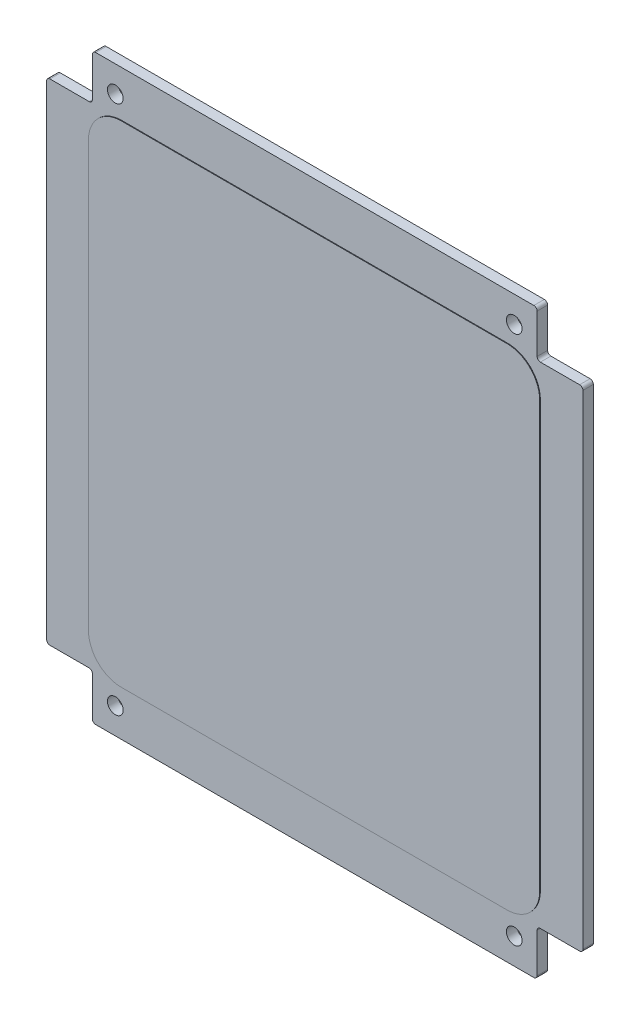
SolidWorks part; units mm, degrees
material "PET"
ref_plane "Front Plane" through (0, 0, 0) normal (0, 0, 1) x (1, 0, 0)
ref_plane "Top Plane" through (0, 0, 0) normal (0, 1, 0) x (1, 0, 0)
ref_plane "Right Plane" through (0, 0, 0) normal (1, 0, 0) x (0, 0, -1)
sketch "Sketch1" plane through (0, 0, 0) normal (0, 0, 1) x (1, 0, 0)
  line L0 (-34, 44) -> (-34, 38)
  line L1 (-33.5, -44.5) -> (33.5, -44.5)
  line L2 (-41, 37) -> (-41, -37)
  line L3 (-33.5, 44.5) -> (33.5, 44.5)
  line L4 (41, -37) -> (41, 37)
  line L5 (34, -44) -> (34, -38)
  line L6 (34.5, -37.5) -> (40.5, -37.5)
  line L7 (-34.5, 37.5) -> (-40.5, 37.5)
  line L8 (34, 44) -> (34, 38)
  line L9 (34.5, 37.5) -> (40.5, 37.5)
  line L10 (-40.5, -37.5) -> (-34.5, -37.5)
  line L11 (-34, -38) -> (-34, -44)
  line L12 (-34.5, -38) -> (34.5, 38) construction
  line L13 (34.5, -38) -> (-34.5, 38) construction
  arc A0 (-33.5, 44.5) -> (-34, 44) centre (-33.5, 44) ccw
  arc A1 (33.5, 44.5) -> (34, 44) centre (33.5, 44) cw
  arc A2 (34, 38) -> (34.5, 37.5) centre (34.5, 38) ccw
  arc A3 (40.5, 37.5) -> (41, 37) centre (40.5, 37) cw
  arc A4 (33.5, -44.5) -> (34, -44) centre (33.5, -44) ccw
  arc A5 (34.5, -37.5) -> (34, -38) centre (34.5, -38) ccw
  arc A6 (40.5, -37.5) -> (41, -37) centre (40.5, -37) ccw
  arc A7 (-34, -44) -> (-33.5, -44.5) centre (-33.5, -44) ccw
  arc A8 (-34, -38) -> (-34.5, -37.5) centre (-34.5, -38) ccw
  arc A9 (-41, -37) -> (-40.5, -37.5) centre (-40.5, -37) ccw
  arc A10 (-40.5, 37.5) -> (-41, 37) centre (-40.5, 37) ccw
  arc A11 (-34.5, 37.5) -> (-34, 38) centre (-34.5, 38) ccw
  point P0 (0, 0)
  dimension "D4" = 0.5
  dimension "D1" = 7
  dimension "D2" = 7
  dimension "D3" = 7
  dimension "D5" = 7
  dimension "D6" = 7
  dimension "D7" = 7
  dimension "D8" = 7
  dimension "D9" = 7
  dimension "D10" = 89
  dimension "D11" = 82
extrude "Boss-Extrude1" add sketch "Sketch1" along normal blind 1.6
sketch "Esboço1" plane through (0, 0, 1.6) normal (0, 0, 1) x (1, 0, 0)
  line L1 (-29.5, -37.5) -> (29.5, -37.5)
  line L2 (-34.5, -32.5) -> (-34.5, 32.5)
  line L3 (-29.5, 37.5) -> (29.5, 37.5)
  line L4 (34.5, -32.5) -> (34.5, 32.5)
  line L5 (-29.5, -32.5) -> (29.5, 32.5) construction
  line L6 (-29.5, 32.5) -> (29.5, -32.5) construction
  arc A0 (-34.5, 32.5) -> (-29.5, 37.5) centre (-29.5, 32.5) cw
  arc A1 (29.5, 37.5) -> (34.5, 32.5) centre (29.5, 32.5) cw
  arc A2 (34.5, -32.5) -> (29.5, -37.5) centre (29.5, -32.5) cw
  arc A3 (-29.5, -37.5) -> (-34.5, -32.5) centre (-29.5, -32.5) cw
  point P0 (0, 0)
  dimension "D1" = 5
  dimension "D2" = 69
  dimension "D3" = 75
extrude "Boss-Extrude2" add sketch "Esboço1" along normal blind 0.1
hole_wizard "M2 Hole1-FixingStructure" positions "Sketch3" profile "Sketch2" hole size "M2" standard "DIN"
sketch "Sketch3" plane through (0, 0, 0) normal (0, 0, -1) x (-1, 0, 0)
  line L0 (-33.5, 44.5) -> (33.5, 44.5) construction
  line L1 (33.5, -44.5) -> (-33.5, -44.5) construction
  line L2 (-41, -37) -> (-41, 37) construction
  line L3 (41, 37) -> (41, -37) construction
  point P0 (-30.5, 40.5)
  point P2 (30.5, 40.5)
  point P4 (-30.5, -40.5)
  point P6 (30.5, -40.5)
  dimension "D1" = 4
  dimension "D2" = 4
  dimension "D3" = 10.5
  dimension "D4" = 10.5
sketch "Sketch2" plane through (30.5, 40.5, 0) normal (1, 0, 0) x (0, 1, 0)
  line L0 (0, 0) -> (0, 200.721)
  line L1 (0, 200.721) -> (1.2, 200)
  line L2 (1.2, 200) -> (1.2, 0)
  line L5 (1.2, 0) -> (0, 0)
  line L10 (0, 200.721) -> (-1.2, 200) construction
  line L11 (0, -6.35) -> (0, 107.95) construction
  dimension "Hole Dia." = 2.4
  dimension "Hole Depth" = 200
  dimension "Drill Angle" = 118
